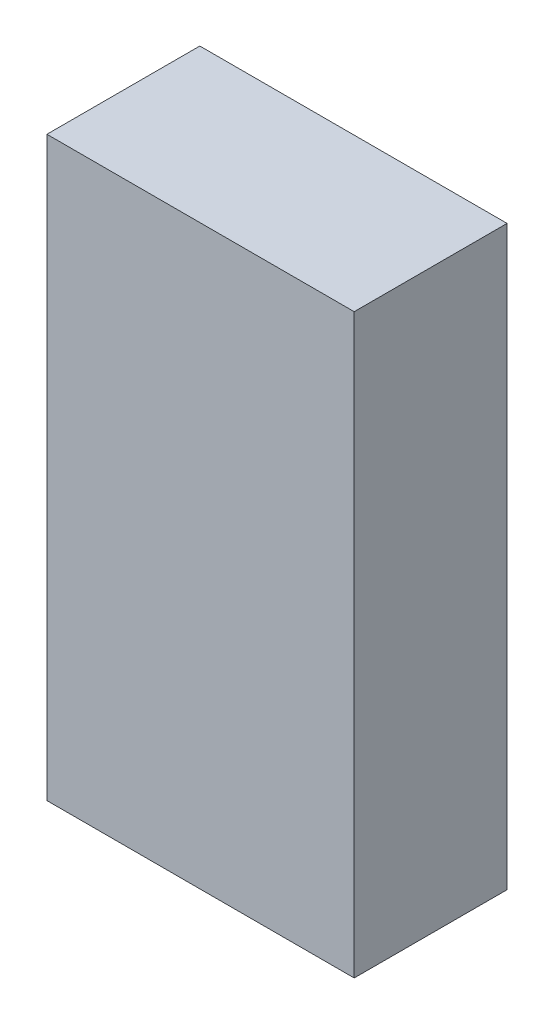
SolidWorks part; units mm, degrees
material "ABS"
ref_plane "Front Plane" through (0, 0, 0) normal (0, 0, 1) x (1, 0, 0)
ref_plane "Top Plane" through (0, 0, 0) normal (0, 1, 0) x (1, 0, 0)
ref_plane "Right Plane" through (0, 0, 0) normal (1, 0, 0) x (0, 0, -1)
ref_plane "P_pack_77_x_" through (-66.3, 0, 0) normal (1, 0, 0) x (0, 0, -1)
sketch "Sketch1" plane through (-66.3, 0, 0) normal (1, 0, 0) x (0, 0, -1)
  line L1 (30.3, -38.5) -> (50.7, -38.5)
  line L2 (30.3, -38.5) -> (30.3, 38.5)
  line L3 (30.3, 38.5) -> (50.7, 38.5)
  line L4 (50.7, -38.5) -> (50.7, 38.5)
extrude "Boss-Extrude1" add sketch "Sketch1" along normal blind 41
